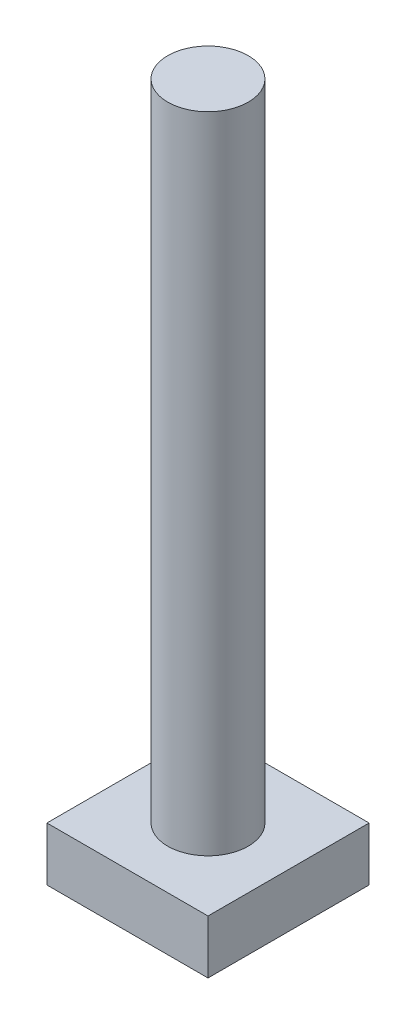
SolidWorks part; units mm, degrees
ref_plane "Front Plane" through (0, 0, 0) normal (0, 0, 1) x (1, 0, 0)
ref_plane "Top Plane" through (0, 0, 0) normal (0, 1, 0) x (1, 0, 0)
ref_plane "Right Plane" through (0, 0, 0) normal (1, 0, 0) x (0, 0, -1)
sketch "Sketch1" plane through (0, 0, 0) normal (0, 1, 0) x (1, 0, 0)
  line L1 (-12, 12) -> (12, 12)
  line L2 (-12, 12) -> (-12, -12)
  line L3 (-12, -12) -> (12, -12)
  line L4 (12, 12) -> (12, -12)
  line L5 (-12, 12) -> (12, -12) construction
  line L6 (-12, -12) -> (12, 12) construction
  point P0 (0, 0)
  dimension "D1" = 24
extrude "Boss-Extrude1" add sketch "Sketch1" along normal mid plane 8
sketch "Sketch2" plane through (0, 4, 0) normal (0, 1, 0) x (1, 0, 0)
  circle A0 centre (0, 0) radius 6
  dimension "D1" = 12
extrude "Boss-Extrude2" add sketch "Sketch2" along normal blind 96
